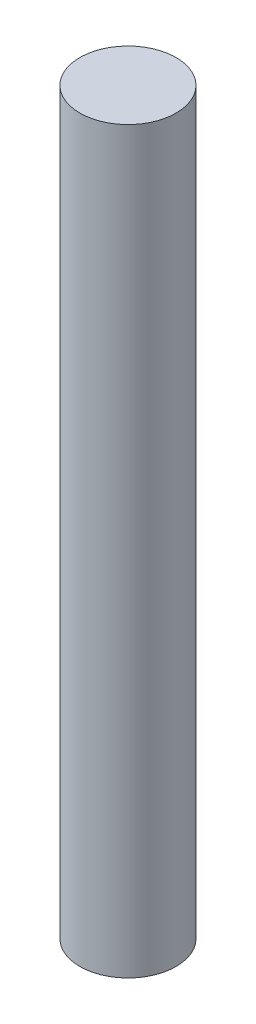
SolidWorks part; units mm, degrees
material "ABS"
ref_plane "Front Plane" through (0, 0, 0) normal (0, 0, 1) x (1, 0, 0)
ref_plane "Top Plane" through (0, 0, 0) normal (0, 1, 0) x (1, 0, 0)
ref_plane "Right Plane" through (0, 0, 0) normal (1, 0, 0) x (0, 0, -1)
sketch "Sketch1" plane through (0, 0, 0) normal (0, 1, 0) x (1, 0, 0)
  circle A0 centre (0, 0) radius 1.55
  dimension "D1" = 3.1
extrude "Boss-Extrude1" add sketch "Sketch1" along normal blind 23.8
